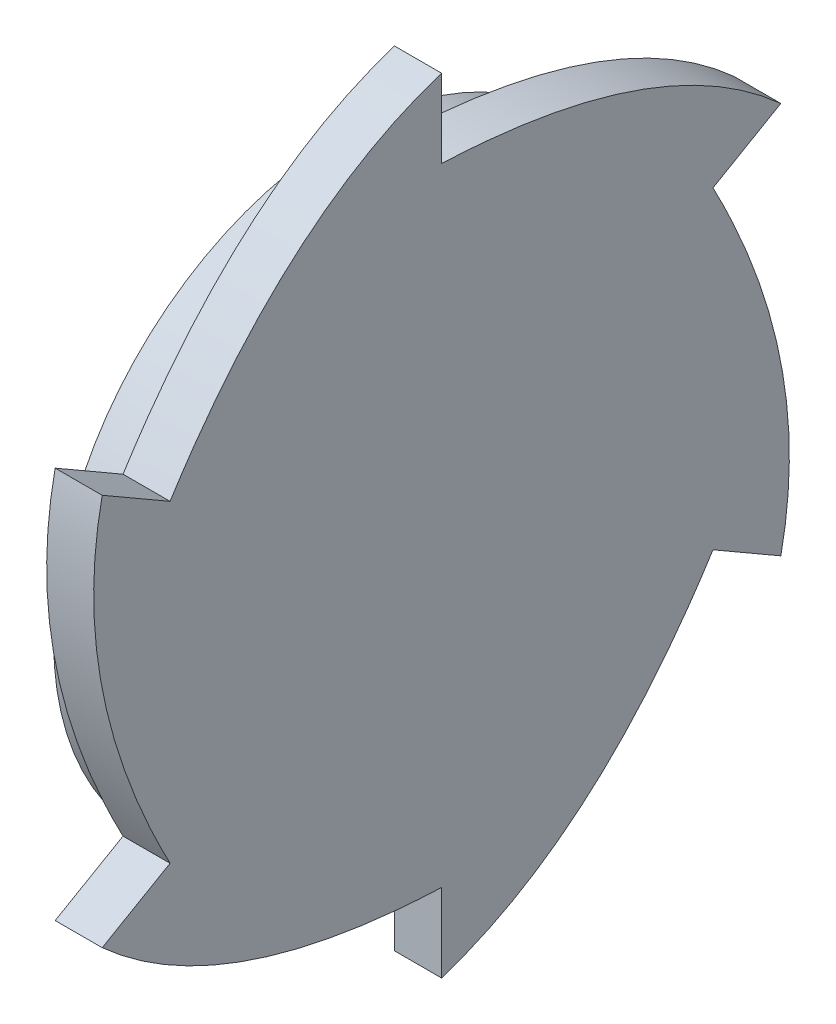
SolidWorks part; units mm, degrees
ref_plane "Front Plane" through (0, 0, 0) normal (0, 0, 1) x (1, 0, 0)
ref_plane "Top Plane" through (0, 0, 0) normal (0, 1, 0) x (1, 0, 0)
ref_plane "Right Plane" through (0, 0, 0) normal (1, 0, 0) x (0, 0, -1)
sketch "Sketch1" plane through (0, 0, 0) normal (1, 0, 0) x (0, 0, -1)
  line L0 (0, 160) -> (0, 200)
  line L1 (138.5641, 80) -> (173.2051, 100)
  line L2 (138.5641, -80) -> (173.2051, -100)
  line L3 (0, -160) -> (0, -200)
  line L4 (-138.5641, -80) -> (-173.2051, -100)
  line L5 (-138.5641, 80) -> (-173.2051, 100)
  spline S0 degree 2 poles (0, 160) (111.5661, 155.6051) (173.2051, 100) knots 0 0 0 0.458761 0.458761 0.458761
  spline S1 degree 2 poles (138.5641, 80) (190.541, -18.8165) (173.2051, -100) knots 0 0 0 0.458761 0.458761 0.458761
  spline S2 degree 2 poles (138.5641, -80) (78.9749, -174.4216) (0, -200) knots 0 0 0 0.458761 0.458761 0.458761
  spline S3 degree 2 poles (0, -160) (-111.5661, -155.6051) (-173.2051, -100) knots 0 0 0 0.458761 0.458761 0.458761
  spline S4 degree 2 poles (-138.5641, -80) (-190.541, 18.8165) (-173.2051, 100) knots 0 0 0 0.458761 0.458761 0.458761
  spline S5 degree 2 poles (-138.5641, 80) (-78.9749, 174.4216) (0, 200) knots 0 0 0 0.458761 0.458761 0.458761
  point P24 (0, 0)
  dimension "D2" = 6
  dimension "D3" = 40
extrude "Boss-Extrude1" add sketch "Sketch1" along normal blind 30
sketch "Sketch2" plane through (0, 0, 0) normal (-1, 0, 0) x (0, 0, 1)
  circle A0 centre (0, 0) radius 150
  dimension "D1" = 300
extrude "Boss-Extrude2" add sketch "Sketch2" along normal blind 30
scale "Scale1" scale about centroid uniform scaling no x scale factor 1 y scale factor 1.25 z scale factor 1.25
